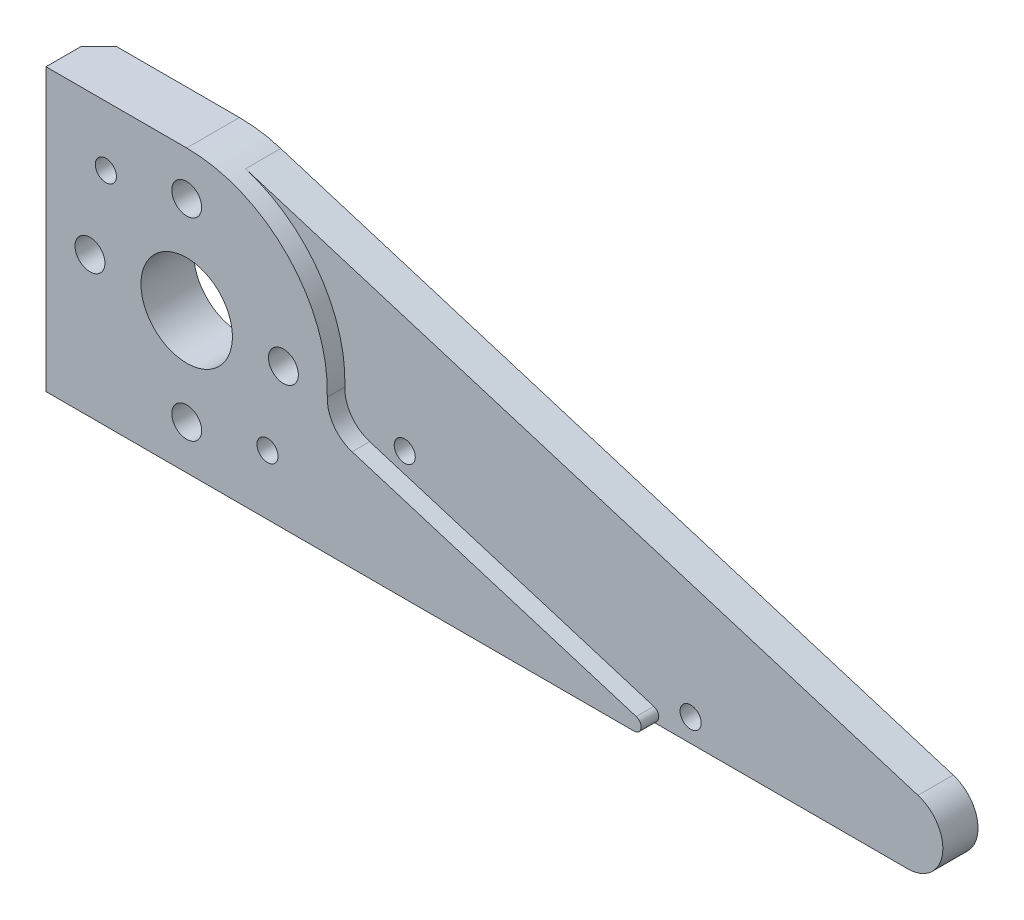
SolidWorks part; units mm, degrees
material "3.3549 (EN-AW 5182)"
ref_plane "Piano frontale" through (0, 0, 0) normal (0, 0, 1) x (1, 0, 0)
ref_plane "Piano superiore" through (0, 0, 0) normal (0, 1, 0) x (1, 0, 0)
ref_plane "Piano destro" through (0, 0, 0) normal (1, 0, 0) x (0, 0, -1)
sketch "Schizzo1" plane through (0, 0, 0) normal (0, 0, 1) x (1, 0, 0)
  line L1 (-40, 40) -> (0, 40)
  line L2 (-40, 40) -> (-40, -40)
  line L3 (-40, -40) -> (0, -40)
  arc A0 (0, -40) -> (0, 40) centre (0, 0) ccw
  dimension "D1" = 80
  dimension "D2" = 40
extrude "Estrusione1" add sketch "Schizzo1" along normal blind 15
chamfer "Smusso1" distance 5 angle 45 1 edges at (-40, 0, 0)
sketch "Schizzo2" plane through (0, 0, 0) normal (0, 0, -1) x (-1, 0, 0)
  circle A0 centre (0, 0) radius 13
  dimension "D1" = 26
extrude "Taglio-Estrusione1" cut sketch "Schizzo2" against normal through all
sketch "Schizzo4" plane through (0, 0, 15) normal (0, 0, 1) x (1, 0, 0)
  line L0 (-37.8193, 37.8193) -> (45.5753, -45.5753) construction
  line L1 (-111.1672, 0) -> (84.1309, 0) construction
  circle A0 centre (0, 0) radius 32.5 construction
  circle A1 centre (-22.981, 22.981) radius 3
  circle A2 centre (22.981, -22.981) radius 3
  dimension "D1" = 65
  dimension "D2" = 6
  dimension "D3" = 45
  dimension "D4" = 6
extrude "Taglio-Estrusione3" cut sketch "Schizzo4" against normal blind 20
sketch "Schizzo5" plane through (0, 0, 0) normal (0, 0, 1) x (1, 0, 0)
  line L0 (-108.9757, 0) -> (49.4015, 0) construction
  circle A1 centre (-22.981, 22.981) radius 5.25
  circle A2 centre (22.981, -22.981) radius 5.25
  dimension "D1" = 10.5
  dimension "D2" = 10.5
extrude "Taglio-Estrusione4" cut sketch "Schizzo5" along normal blind 8.5
sketch "Schizzo6" plane through (0, 0, 0) normal (0, 0, -1) x (-1, 0, 0)
  line L0 (-43.0805, 0) -> (35.0457, 0) construction
  line L1 (0, 33.5196) -> (0, -32.8544) construction
  circle A3 centre (0, 0) radius 27.5 construction
  circle A4 centre (27.5, 0) radius 2.5
  circle A5 centre (0, -27.5) radius 2.5
  circle A6 centre (-27.5, 0) radius 2.5
  circle A7 centre (0, 27.5) radius 2.5
  dimension "D1" = 5
  dimension "D2" = 5
  dimension "D3" = 5
  dimension "D4" = 5
  dimension "D5" = 55
extrude "Taglio-Estrusione5" cut sketch "Schizzo6" against normal blind 20
sketch "Schizzo7" plane through (0, 0, 15) normal (0, 0, 1) x (1, 0, 0)
  circle A0 centre (0, 27.5) radius 4.25
  circle A1 centre (-27.5, 0) radius 4.25
  circle A2 centre (27.5, 0) radius 4.25
  circle A3 centre (0, -27.5) radius 4.25
  dimension "D1" = 8.5
  dimension "D2" = 8.5
  dimension "D3" = 8.5
  dimension "D4" = 8.5
extrude "Taglio-Estrusione6" cut sketch "Schizzo7" against normal blind 6
sketch "Schizzo8" plane through (0, 0, 15) normal (0, 0, 1) x (1, 0, 0)
  line L0 (11.7359, 38.2396) -> (202.934, -20.4401)
  line L1 (0, -40) -> (200, -40)
  arc A0 (0, -40) -> (0, 40) centre (0, 0) ccw construction
  arc A1 (0, -40) -> (11.7359, 38.2396) centre (0, 0) ccw
  arc A2 (200, -40) -> (202.934, -20.4401) centre (200, -30) ccw
  dimension "D1" = 10
  dimension "D2" = 200
extrude "Estrusione2" add sketch "Schizzo8" against normal blind 15
sketch "Schizzo9" plane through (0, 0, 15) normal (0, 0, 1) x (1, 0, 0)
  line L2 (140.5583, -40) -> (200, -40)
  line L3 (11.7359, 38.2396) -> (202.934, -20.4401)
  line L5 (140.5583, -40) -> (47.0358, -11.2974)
  line L10 (-40, -40) -> (200, -40) construction
  line L12 (202.934, -20.4401) -> (11.7359, 38.2396) construction
  arc A0 (39.9758, -1.39) -> (11.7359, 38.2396) centre (0, 0) ccw
  arc A1 (200, -40) -> (202.934, -20.4401) centre (200, -30) ccw construction
  arc A2 (200, -40) -> (202.934, -20.4401) centre (200, -30) ccw
  arc A3 (47.0358, -11.2974) -> (39.9758, -1.39) centre (49.9698, -1.7375) cw
  dimension "D6" = 80
  dimension "D1" = 10
  dimension "D2" = 37
extrude "Taglio-Estrusione7" cut sketch "Schizzo9" against normal blind 5
sketch "Schizzo10" plane through (0, 0, 15) normal (0, 0, 1) x (1, 0, 0)
  line L0 (110.4408, -33.5) -> (150.5014, -33.5) construction
  line L1 (57, -8.6484) -> (138.2859, -33.5) construction
  line L3 (57, 36.239) -> (57, -67.8658) construction
  line L4 (-40, -40) -> (140.5583, -40) construction
  circle A0 centre (57, -8.6484) radius 3
  circle A1 centre (138.2859, -33.5) radius 3
  dimension "D5" = 6
  dimension "D6" = 6
  dimension "D1" = 17
  dimension "D2" = 85
  dimension "D3" = 6.5
  dimension "D4" = 57
extrude "Taglio-Estrusione8" cut sketch "Schizzo10" against normal blind 10
fillet "Raccordo1" radius 2 1 edges at (140.5583, -40, 12.5)
